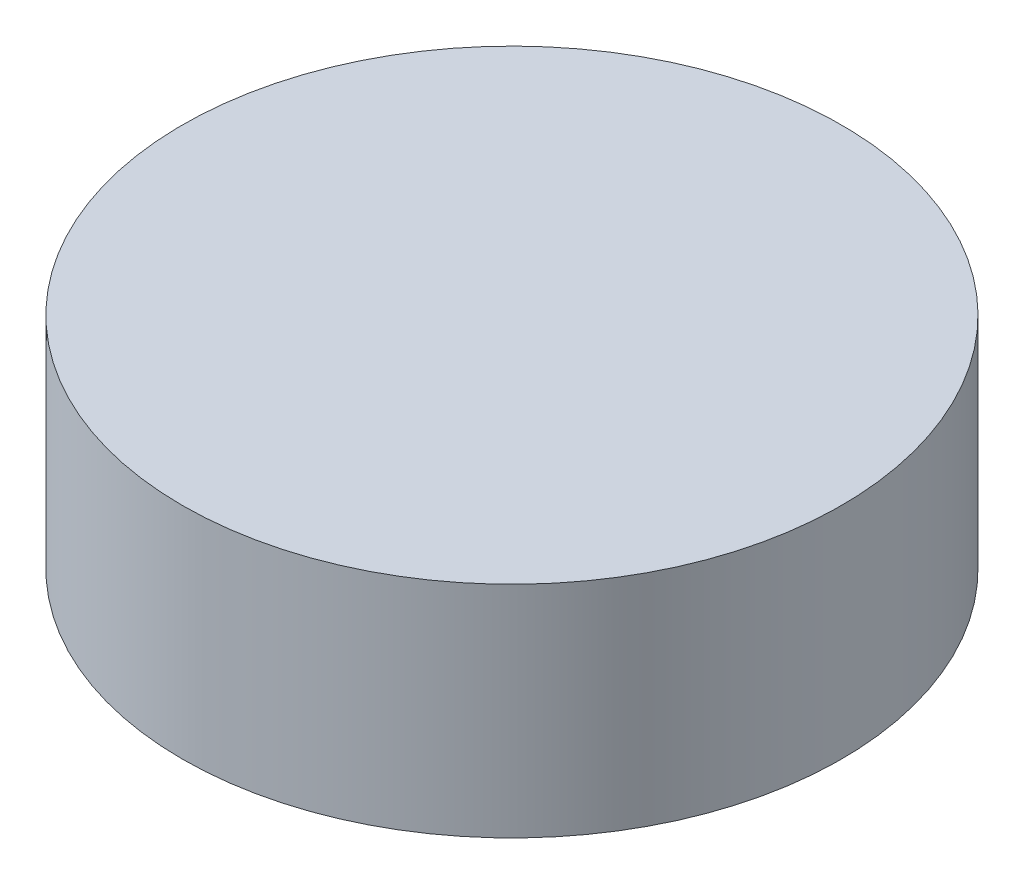
SolidWorks part; units mm, degrees
ref_plane "Front Plane" through (0, 0, 0) normal (0, 0, 1) x (1, 0, 0)
ref_plane "Top Plane" through (0, 0, 0) normal (0, 1, 0) x (1, 0, 0)
ref_plane "Right Plane" through (0, 0, 0) normal (1, 0, 0) x (0, 0, -1)
sketch "Sketch1" plane through (0, 0, 0) normal (0, 1, 0) x (1, 0, 0)
  circle A0 centre (0, 0) radius 60
extrude "Boss-Extrude1" add sketch "Sketch1" along normal blind 40
